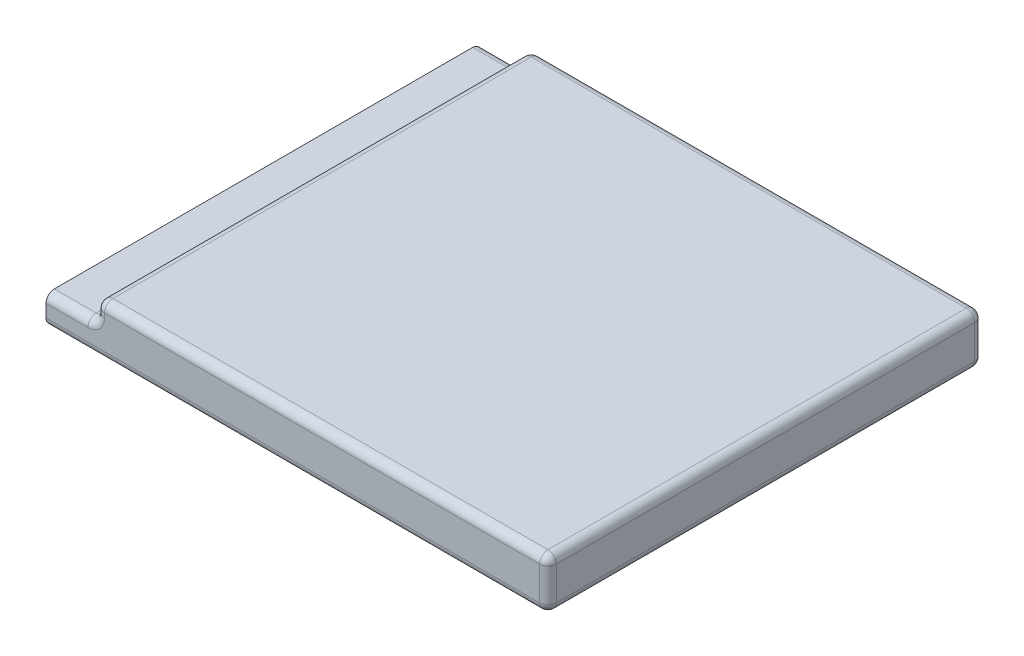
SolidWorks part; units mm, degrees
material "Custom Plastic"
ref_plane "Front Plane" through (0, 0, 0) normal (0, 0, 1) x (1, 0, 0)
ref_plane "Top Plane" through (0, 0, 0) normal (0, 1, 0) x (1, 0, 0)
ref_plane "Right Plane" through (0, 0, 0) normal (1, 0, 0) x (0, 0, -1)
sketch "Sketch2" plane through (0, 0, 0) normal (0, 1, 0) x (1, 0, 0)
  line L1 (-18.8789, 20.4764) -> (41.1211, 20.4764)
  line L2 (-18.8789, 20.4764) -> (-18.8789, -31.5236)
  line L3 (-18.8789, -31.5236) -> (41.1211, -31.5236)
  line L4 (41.1211, 20.4764) -> (41.1211, -31.5236)
extrude "Boss-Extrude1" add sketch "Sketch2" along normal blind 6
sketch "Sketch3" plane through (0, 6, 0) normal (0, 1, 0) x (1, 0, 0)
  line L2 (41.1211, 20.4764) -> (-18.8789, 20.4764) construction
  line L3 (-12.8789, 20.4764) -> (-18.8789, 20.4764)
  line L4 (-12.8789, 20.4764) -> (-12.8789, -31.5236)
  line L5 (-12.8789, -31.5236) -> (-18.8789, -31.5236)
  line L6 (-18.8789, 20.4764) -> (-18.8789, -31.5236)
extrude "Cut-Extrude1" cut sketch "Sketch3" against normal blind 2.5
fillet "Fillet1" radius 1 14 edges at (-15.8789, 3.5, 31.5236) (-15.8789, 3.5, -20.4764) (-12.8789, 3.5, 5.5236) (41.1211, 3, -20.4764) (41.1211, 3, 31.5236) (-12.8789, 4.75, 31.5236) (-12.8789, 4.75, -20.4764) (11.1211, 0, -20.4764) (41.1211, 0, 5.5236) (11.1211, 0, 31.5236) (41.1211, 6, 5.5236) (14.1211, 6, -20.4764) (-12.8789, 6, 5.5236) (14.1211, 6, 31.5236)
